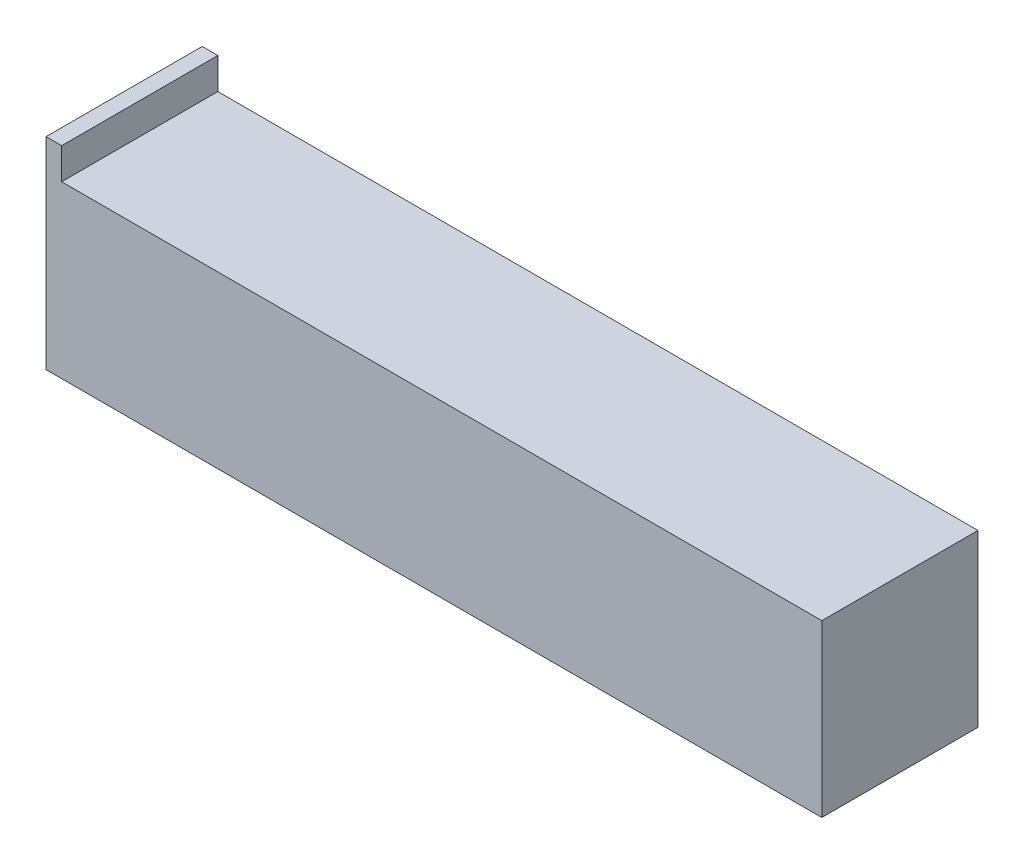
SolidWorks part; units mm, degrees
ref_plane "Front Plane" through (0, 0, 0) normal (0, 0, 1) x (1, 0, 0)
ref_plane "Top Plane" through (0, 0, 0) normal (0, 1, 0) x (1, 0, 0)
ref_plane "Right Plane" through (0, 0, 0) normal (1, 0, 0) x (0, 0, -1)
sketch "Sketch1" plane through (0, 0, 0) normal (0, 0, 1) x (1, 0, 0)
  line L1 (0, 0) -> (75.692, 0)
  line L2 (0, 0) -> (0, -16.637)
  line L3 (0, -16.637) -> (75.692, -16.637)
  line L4 (75.692, 0) -> (75.692, -16.637)
  line L6 (0, 0) -> (0, 3.048)
  line L7 (0, 3.048) -> (1.524, 3.048)
  line L8 (1.524, 0) -> (1.524, 3.048)
  dimension "D1" = 75.692
  dimension "D2" = 74.168
  dimension "D3" = 16.637
  dimension "D4" = 3.048
extrude "Boss-Extrude1" add sketch "Sketch1" along normal blind 15.24 contours L4 L1 L2 L3 | L1 L8 L7 L6
